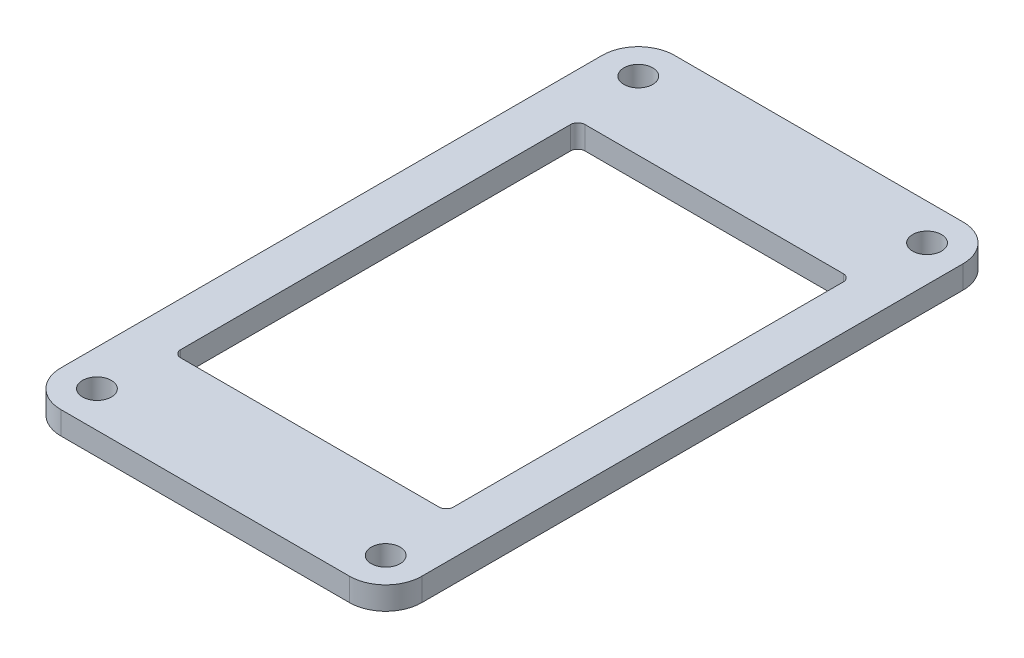
SolidWorks part; units mm, degrees
ref_plane "Front Plane" through (0, 0, 0) normal (0, 0, 1) x (1, 0, 0)
ref_plane "Top Plane" through (0, 0, 0) normal (0, 1, 0) x (1, 0, 0)
ref_plane "Right Plane" through (0, 0, 0) normal (1, 0, 0) x (0, 0, -1)
sketch "Sketch1" plane through (0, 0, 0) normal (0, 1, 0) x (1, 0, 0)
  line L1 (0, 0) -> (50, 0)
  line L2 (0, 0) -> (0, 85)
  line L3 (0, 85) -> (50, 85)
  line L4 (50, 0) -> (50, 85)
  dimension "D1" = 50
  dimension "D2" = 85
extrude "Boss-Extrude1" add sketch "Sketch1" along normal blind 3.175
sketch "Sketch3" plane through (0, 3.175, 0) normal (0, 1, 0) x (1, 0, 0)
  line L0 (25, 0) -> (25, 85) construction
  line L1 (6.109, 14.498) -> (43.891, 14.498)
  line L2 (6.109, 14.498) -> (6.109, 70.502)
  line L3 (6.109, 70.502) -> (43.891, 70.502)
  line L4 (43.891, 14.498) -> (43.891, 70.502)
  line L5 (0, 0) -> (50, 0) construction
  line L6 (50, 85) -> (0, 85) construction
  line L7 (0, 42.5) -> (50, 42.5) construction
  line L8 (0, 85) -> (0, 0) construction
  line L9 (50, 0) -> (50, 85) construction
  point P16 (43.891, 42.5)
  point P17 (25, 14.498)
  dimension "D1" = 56.004
  dimension "D2" = 37.782
extrude "Cut-Extrude1" cut sketch "Sketch3" against normal through all
fillet "Fillet2" radius 1 4 edges at (43.891, 1.5875, -70.502) (43.891, 1.5875, -14.498) (6.109, 1.5875, -14.498) (6.109, 1.5875, -70.502)
fillet "Fillet3" radius 5 4 edges at (0, 1.5875, -85) (50, 1.5875, -85) (50, 1.5875, 0) (0, 1.5875, 0)
sketch "Sketch4" plane through (0, 3.175, 0) normal (0, 1, 0) x (1, 0, 0)
  circle A0 centre (5, 5) radius 2
  circle A1 centre (45, 5) radius 2
  circle A2 centre (45, 80) radius 2
  circle A3 centre (5, 80) radius 2
  dimension "D1" = 4
  dimension "D2" = 4
  dimension "D3" = 4
  dimension "D4" = 4
extrude "Cut-Extrude2" cut sketch "Sketch4" against normal through all
